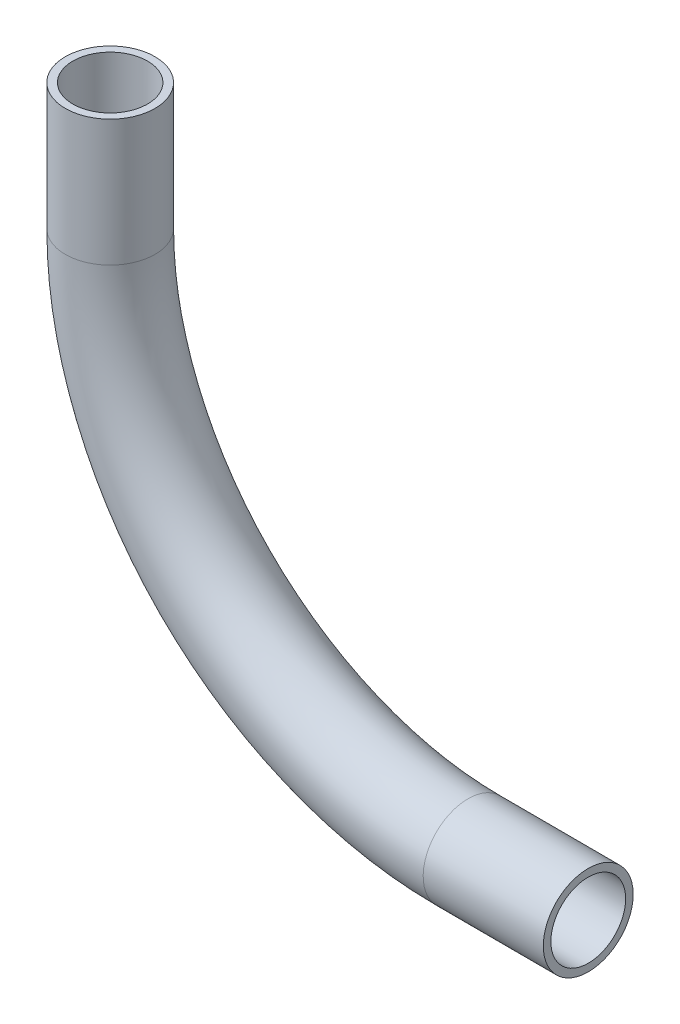
SolidWorks part; units mm, degrees
ref_plane "Front Plane" through (0, 0, 0) normal (0, 0, 1) x (1, 0, 0)
ref_plane "Top Plane" through (0, 0, 0) normal (0, 1, 0) x (1, 0, 0)
ref_plane "Right Plane" through (0, 0, 0) normal (1, 0, 0) x (0, 0, -1)
sketch3d "3DSketch1"
  line L0 (44.5241, -643.3154, 354.9277) -> (44.5241, -661.2164, 354.9277)
  line L1 (95.324, -712.0164, 355.047) -> (112.3727, -712.0164, 355.0871)
  arc A2 (44.5241, -661.2164, 354.9277) -> (95.324, -712.0164, 355.047) centre (95.324, -661.2164, 355.047) ccw
  point P0 (44.5241, -661.2164, 354.9277)
  point P13 (44.5241, -712.0164, 354.9277)
  point P14 (95.2047, -661.2164, 405.8469)
  dimension "D1" = 50.8
other "Pipe 0.5 SCH 40(1)"
ref_plane "Plane1" through (44.5241, -643.3154, 354.9277) normal (0, -1, 0) x (1, 0, 0)
sketch "Sketch1" plane through (44.5241, -643.3154, 354.9277) normal (0, -1, 0) x (1, 0, 0)
  circle A0 centre (0, 0) radius 5.2832
  circle A1 centre (0, 0) radius 6.35
  point P5 (0, 0)
  dimension "In_dia" = 10.5664
  dimension "Out_dia" = 12.7
